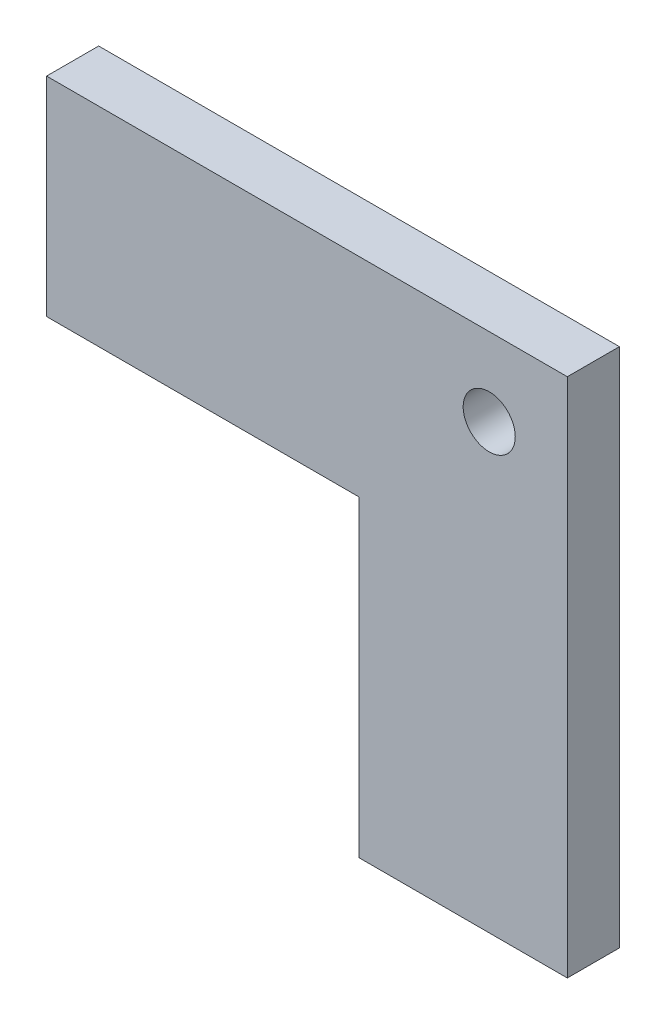
SolidWorks part; units mm, degrees
ref_plane "Front Plane" through (0, 0, 0) normal (0, 0, 1) x (1, 0, 0)
ref_plane "Top Plane" through (0, 0, 0) normal (0, 1, 0) x (1, 0, 0)
ref_plane "Right Plane" through (0, 0, 0) normal (1, 0, 0) x (0, 0, -1)
sketch "Sketch1" plane through (0, 0, 0) normal (0, 0, 1) x (1, 0, 0)
  line L1 (-35.1034, 99.5309) -> (91.8966, 99.5309)
  line L2 (-35.1034, 99.5309) -> (-35.1034, -27.4691)
  line L3 (-35.1034, -27.4691) -> (91.8966, -27.4691)
  line L4 (91.8966, 99.5309) -> (91.8966, -27.4691)
  dimension "D1" = 127
  dimension "D2" = 127
extrude "Boss-Extrude1" add sketch "Sketch1" against normal blind 12.7
ref_plane "Plane7" through (91.8966, 99.5309, -12.7) normal (0, 1, 0) x (1, 0, 0)
sketch "Sketch2" plane through (91.8966, 99.5309, -12.7) normal (0, 1, 0) x (1, 0, 0)
  line L1 (-8.1024, 499860.3) -> (-8.1064, 499987.3)
  dimension "D1" = 127
sketch "Sketch3" plane through (0, 0, 0) normal (0, 0, 1) x (1, 0, 0)
  line L0 (-35.1034, 99.5309) -> (-35.1034, -27.4691) construction
  line L1 (-35.1034, -27.4691) -> (41.0966, -27.4691)
  line L2 (-35.1034, -27.4691) -> (-35.1034, 48.7309)
  line L3 (-35.1034, 48.7309) -> (41.0966, 48.7309)
  line L4 (41.0966, -27.4691) -> (41.0966, 48.7309)
  point P6 (0, 0)
  point P7 (-35.1034, -27.4691)
  point P8 (-35.1034, -27.4691)
  dimension "D1" = 76.2
  dimension "D2" = 76.2
extrude "Cut-Extrude1" cut sketch "Sketch3" against normal through all both
sketch "Sketch4" plane through (0, 0, 0) normal (0, 0, 1) x (1, 0, 0)
  line L0 (91.8966, -27.4691) -> (91.8966, 99.5309) construction
  line L1 (91.8966, 99.5309) -> (-35.1034, 99.5309) construction
  circle A0 centre (72.8466, 80.4809) radius 6.35
  dimension "D1" = 12.7
  dimension "D2" = 19.05
  dimension "D3" = 19.05
extrude "Cut-Extrude2" cut sketch "Sketch4" against normal through all both
